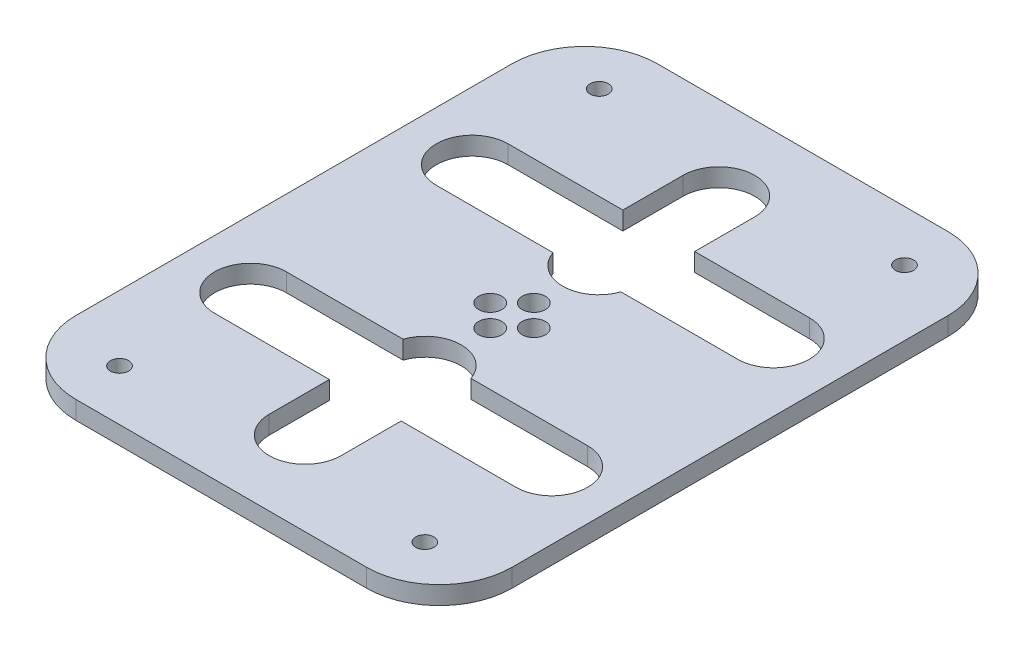
SolidWorks part; units mm, degrees
ref_plane "前视基准面" through (0, 0, 0) normal (0, 0, 1) x (1, 0, 0)
ref_plane "上视基准面" through (0, 0, 0) normal (0, 1, 0) x (1, 0, 0)
ref_plane "右视基准面" through (0, 0, 0) normal (1, 0, 0) x (0, 0, -1)
sketch "草图1" plane through (0, 0, 0) normal (0, 1, 0) x (1, 0, 0)
  line L0 (0, 0) -> (0, 19.1284) construction
  line L1 (-30, -40) -> (30, -40)
  line L2 (-30, -40) -> (-30, 40)
  line L3 (-30, 40) -> (30, 40)
  line L4 (30, -40) -> (30, 40)
  line L5 (-30, -40) -> (30, 40) construction
  line L6 (-30, 40) -> (30, -40) construction
  line L7 (0, 0) -> (15.4128, 0) construction
  circle A0 centre (21, 33) radius 1.25
  circle A1 centre (-21, 33) radius 1.25
  circle A2 centre (-21, -33) radius 1.25
  circle A3 centre (21, -33) radius 1.25
  circle A4 centre (0, 3) radius 1.6
  circle A5 centre (3, 0) radius 1.6
  circle A6 centre (0, -3) radius 1.6
  circle A7 centre (-3, 0) radius 1.6
  point P0 (0, 0)
  dimension "D3" = 21
  dimension "D5" = 3
  dimension "D6" = 3
  dimension "D1" = 80
  dimension "D2" = 60
  dimension "D4" = 33
extrude "凸台-拉伸1" add sketch "草图1" along normal blind 2.5
fillet "圆角1" radius 10 4 edges at (-30, 1.25, -40) (-30, 1.25, 40) (30, 1.25, 40) (30, 1.25, -40)
sketch "草图2" plane through (0, 2.5, 0) normal (0, 1, 0) x (1, 0, 0)
  line L0 (0, 0) -> (0, 17.7233) construction
  line L1 (0, 0) -> (18.7975, 0) construction
  line L2 (-20.7309, 15.2528) -> (20.7309, 15.2528) construction
  line L3 (-20.7309, 20.1939) -> (20.7309, 20.1939)
  line L4 (-20.7309, 10.3118) -> (20.7309, 10.3118)
  line L5 (-20.7309, -15.2528) -> (20.7309, -15.2528) construction
  line L6 (-20.7309, -20.1939) -> (20.7309, -20.1939)
  line L7 (-20.7309, -10.3118) -> (20.7309, -10.3118)
  arc A0 (-20.7309, 20.1939) -> (-20.7309, 10.3118) centre (-20.7309, 15.2528) ccw
  arc A1 (20.7309, 10.3118) -> (20.7309, 20.1939) centre (20.7309, 15.2528) ccw
  arc A2 (-20.7309, -20.1939) -> (-20.7309, -10.3118) centre (-20.7309, -15.2528) cw
  arc A3 (20.7309, -10.3118) -> (20.7309, -20.1939) centre (20.7309, -15.2528) cw
  point P6 (0, 15.2528)
  point P13 (0, -15.2528)
extrude "切除-拉伸1" cut sketch "草图2" against normal blind 2.5
sketch "草图3" plane through (0, 2.5, 0) normal (0, 1, 0) x (1, 0, 0)
  line L0 (0, 11.923) -> (0, 28.4648) construction
  line L1 (20.7309, 20.1939) -> (-20.7309, 20.1939) construction
  line L2 (-4.9411, 11.923) -> (-4.9411, 28.4648)
  line L3 (4.9411, 11.923) -> (4.9411, 28.4648)
  line L4 (0, 0) -> (11.6007, 0) construction
  line L5 (0, -11.923) -> (0, -28.4648) construction
  line L6 (-4.9411, -11.923) -> (-4.9411, -28.4648)
  line L7 (4.9411, -11.923) -> (4.9411, -28.4648)
  arc A0 (-4.9411, 11.923) -> (4.9411, 11.923) centre (0, 11.923) ccw
  arc A1 (4.9411, 28.4648) -> (-4.9411, 28.4648) centre (0, 28.4648) ccw
  arc A2 (-4.9411, -11.923) -> (4.9411, -11.923) centre (0, -11.923) cw
  arc A3 (4.9411, -28.4648) -> (-4.9411, -28.4648) centre (0, -28.4648) cw
  point P5 (0, 20.1939)
  point P14 (0, -20.1939)
extrude "切除-拉伸2" cut sketch "草图3" against normal blind 2.5
